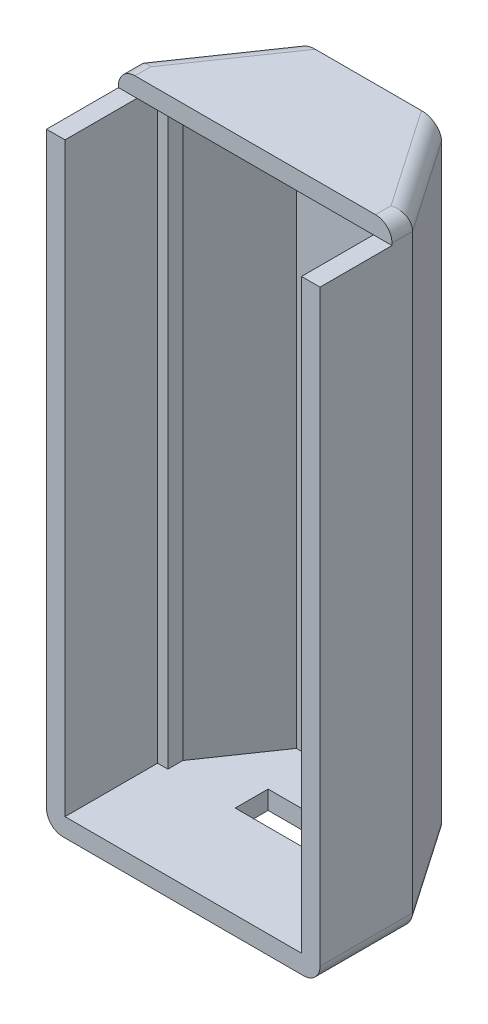
SolidWorks part; units mm, degrees
ref_plane "Спереди" through (0, 0, 0) normal (0, 0, 1) x (1, 0, 0)
ref_plane "Сверху" through (0, 0, 0) normal (0, 1, 0) x (1, 0, 0)
ref_plane "Справа" through (0, 0, 0) normal (1, 0, 0) x (0, 0, -1)
sketch "Sketch1" plane through (0, 0, 0) normal (0, 1, 0) x (1, 0, 0)
  line L0 (-11.5, 0) -> (11.5, 0) construction
  line L1 (11.5, 0) -> (11.5, 9)
  line L2 (10.5, 10.4545) -> (6, 17)
  line L3 (-11.5, 0) -> (-11.5, 9)
  line L4 (-10.5, 10.4545) -> (-6, 17)
  line L5 (-6, 17) -> (6, 17)
  line L6 (-13.3, 0) -> (-13.3, 9)
  line L7 (-13.3, 9) -> (-7.3314, 17.6816)
  line L8 (-7.3314, 17.6816) -> (-7.1125, 18)
  line L9 (-7.1125, 18) -> (7.1125, 18)
  line L10 (7.1125, 18) -> (7.3686, 17.6275)
  line L11 (7.3686, 17.6275) -> (13.3, 9)
  line L12 (13.3, 9) -> (13.3, 0)
  line L13 (13.3, 0) -> (11.5, 0)
  line L14 (-11.5, 0) -> (-13.3, 0)
  line L15 (-11.5, 9) -> (-10.5, 9)
  line L16 (-10.5, 9) -> (-10.5, 10.4545)
  line L17 (11.5, 9) -> (10.5, 9)
  line L18 (10.5, 9) -> (10.5, 10.4545)
  point P5 (0, 0)
  point P10 (0, 17)
  dimension "D1" = 23
  dimension "D2" = 9
  dimension "D5" = 12
  dimension "D6" = 8
  dimension "D3" = 1.8
  dimension "D4" = 1.8
  dimension "D7" = 1
  dimension "D8" = 1
  dimension "D9" = 1
extrude "Boss-Extrude1" add sketch "Sketch1" along normal blind 57
sketch "Sketch4" plane through (0, 0, -18) normal (0, 0, -1) x (-1, 0, 0)
  line L1 (-5.7, 16.7) -> (0.8, 16.7)
  line L2 (-5.7, 16.7) -> (-5.7, 8.2)
  line L3 (-5.7, 8.2) -> (0.8, 8.2)
  line L4 (0.8, 16.7) -> (0.8, 8.2)
  dimension "D1" = 8.5
  dimension "D2" = 6.5
  dimension "D3" = 8.2
  dimension "D4" = 5.7
extrude "Cut-Extrude1" cut sketch "Sketch4" against normal through all
sketch "Sketch2" plane through (0, 0, 0) normal (0, -1, 0) x (1, 0, 0)
  line L0 (-13.3, 0) -> (-13.3, -9)
  line L1 (-13.3, -9) -> (-7.1125, -18)
  line L2 (-7.1125, -18) -> (7.1125, -18)
  line L3 (7.1125, -18) -> (13.3, -9)
  line L4 (13.3, -9) -> (13.3, 0)
  line L5 (13.3, 0) -> (-13.3, 0)
extrude "Boss-Extrude2" add sketch "Sketch2" along normal blind 1.8
sketch "Sketch5" plane through (0, -1.8, 0) normal (0, -1, 0) x (1, 0, 0)
  line L1 (-3.95, -9) -> (3.95, -9)
  line L2 (-3.95, -9) -> (-3.95, -12.2)
  line L3 (-3.95, -12.2) -> (3.95, -12.2)
  line L4 (3.95, -9) -> (3.95, -12.2)
  point P4 (-3.8695, -3.0379)
  point P5 (0, -9)
  point P9 (0, 0)
  point P10 (0, 0)
  point P11 (0, 0)
  dimension "D1" = 3.2
  dimension "D2" = 7.9
extrude "Cut-Extrude2" cut sketch "Sketch5" against normal through all
sketch "Sketch3" plane through (0, 57, 0) normal (0, 1, 0) x (1, 0, 0)
  line L0 (-13.3, 9) -> (-7.1125, 18)
  line L1 (-7.1125, 18) -> (7.1125, 18)
  line L2 (13.3, 9) -> (7.1125, 18) construction
  line L3 (7.1125, 18) -> (-7.1125, 18) construction
  line L4 (7.1125, 18) -> (13.3, 9)
  line L5 (13.3, 9) -> (13.3, 7)
  line L6 (13.3, 0) -> (13.3, 9) construction
  line L7 (13.3, 7) -> (-13.3, 7)
  line L8 (-13.3, 9) -> (-13.3, 0) construction
  line L9 (-13.3, 7) -> (-13.3, 9)
  dimension "D1" = 2
extrude "Boss-Extrude3" add sketch "Sketch3" along normal blind 1.8
fillet "Fillet1" radius 1.6 8 edges at (13.3, 58.8, -8) (10.2063, 58.8, -13.5) (-10.2062, 58.8, -13.5) (-13.3, 58.8, -8) (-13.3, -1.8, -4.5) (-10.2062, -1.8, -13.5) (10.2063, -1.8, -13.5) (13.3, -1.8, -4.5)
equation "\"D9@Sketch1\"=\"D8@Sketch1\""
equation "\"D4@Sketch1\"=\"D3@Sketch1\""
